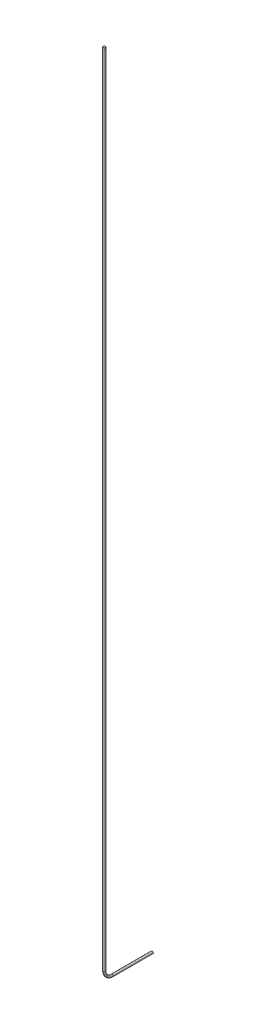
SolidWorks part; units mm, degrees
ref_plane "正面" through (0, 0, 0) normal (0, 0, 1) x (1, 0, 0)
ref_plane "平面" through (0, 0, 0) normal (0, 1, 0) x (1, 0, 0)
ref_plane "右側面" through (0, 0, 0) normal (1, 0, 0) x (0, 0, -1)
sketch "ｽｹｯﾁ1" plane through (0, 0, 0) normal (0, 0, 1) x (1, 0, 0)
  circle A0 centre (0, 0) radius 0.7
  dimension "D1" = 1.4
extrude "ﾎﾞｽ - 押し出し1" add sketch "ｽｹｯﾁ1" along normal blind 20
sketch "ｽｹｯﾁ2" plane through (0, 0, 20) normal (0, 0, 1) x (1, 0, 0)
  circle A1 centre (0, 0) radius 0.7
  circle A2 centre (0, 0) radius 0.7
  dimension "D1" = 0
sketch "ｽｹｯﾁ3" plane through (0, 0, 0) normal (1, 0, 0) x (0, 0, -1)
  line L0 (-20, 0) -> (-25, 0)
  line L1 (-20, 0.7) -> (-20, -0.7) construction
  line L2 (-30, 5) -> (-30, 505)
  line L3 (-20, 0.7) -> (-20, -0.7) construction
  arc A0 (-25, 0) -> (-30, 5) centre (-25, 5) cw
  point P8 (-30, 0)
  dimension "D2" = 5
  dimension "D1" = 10
  dimension "D3" = 500
sweep "ｽｲｰﾌﾟ1" add profiles "ｽｹｯﾁ2" path "ｽｹｯﾁ3"
